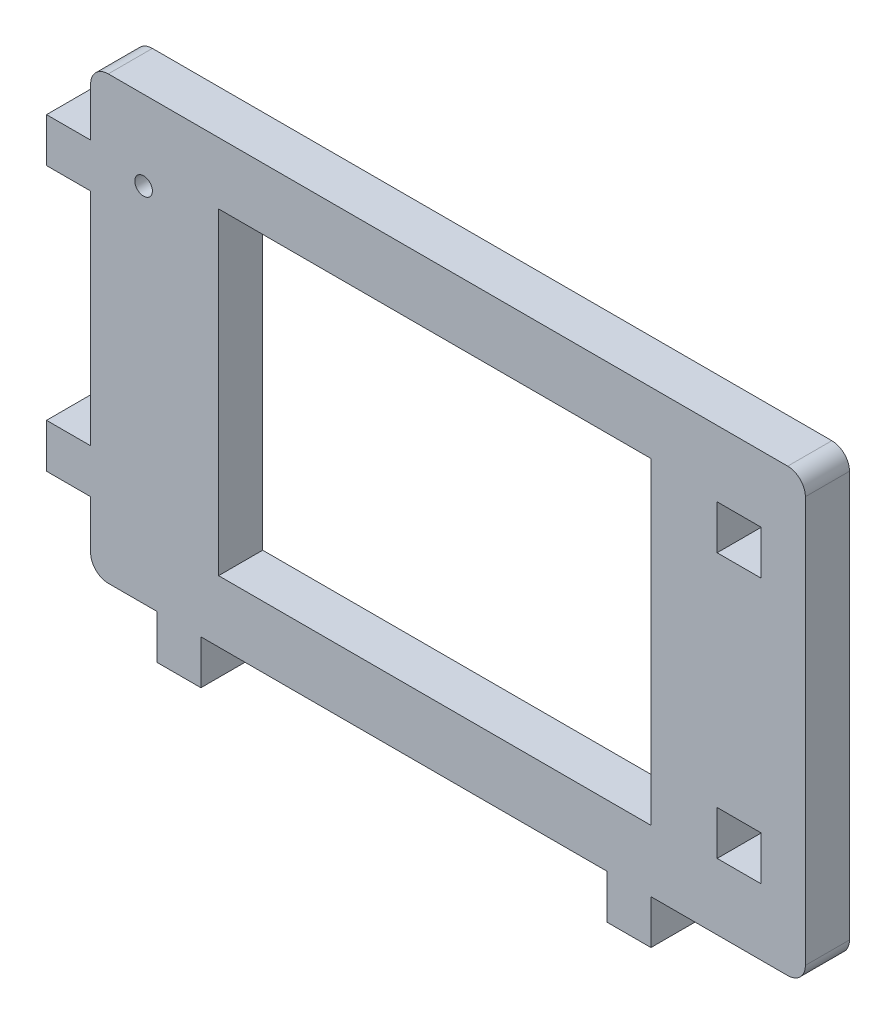
SolidWorks part; units mm, degrees
ref_plane "Plan de face" through (0, 0, 0) normal (0, 0, 1) x (1, 0, 0)
ref_plane "Plan de dessus" through (0, 0, 0) normal (0, 1, 0) x (1, 0, 0)
ref_plane "Plan de droite" through (0, 0, 0) normal (1, 0, 0) x (0, 0, -1)
sketch "Esquisse1" plane through (0, 0, 0) normal (0, 0, 1) x (1, 0, 0)
  line L0 (0, 25) -> (71, 25) construction
  line L1 (0, 0) -> (7.5, 0)
  line L2 (0, 0) -> (0, 7.5)
  line L3 (0, 50) -> (71, 50)
  line L4 (71, 0) -> (71, 7.5) construction
  line L5 (0, 12.5) -> (-5, 12.5)
  line L7 (0, 7.5) -> (-5, 7.5)
  line L8 (-5, 12.5) -> (-5, 7.5)
  line L9 (35.5, 0) -> (35.5, 50) construction
  line L10 (0, 37.5) -> (-5, 37.5)
  line L11 (-5, 37.5) -> (-5, 42.5)
  line L12 (0, 42.5) -> (-5, 42.5)
  line L13 (58.5, 0) -> (58.5, -5)
  line L15 (7.5, 0) -> (7.5, -5)
  line L16 (7.5, -5) -> (12.5, -5)
  line L17 (12.5, 0) -> (12.5, -5)
  line L18 (63.5, -5) -> (58.5, -5)
  line L19 (63.5, 0) -> (63.5, -5)
  line L20 (71, 7.5) -> (76, 7.5)
  line L21 (76, 12.5) -> (76, 7.5)
  line L22 (71, 12.5) -> (76, 12.5)
  line L23 (71, 37.5) -> (76, 37.5)
  line L24 (76, 37.5) -> (76, 42.5)
  line L25 (71, 42.5) -> (76, 42.5)
  line L26 (0, 42.5) -> (0, 50)
  line L27 (0, 12.5) -> (0, 37.5)
  line L28 (12.5, 0) -> (58.5, 0)
  line L29 (63.5, 0) -> (71, 0)
  line L30 (71, 12.5) -> (71, 37.5) construction
  line L31 (71, 42.5) -> (71, 50) construction
  line L32 (71, 50) -> (81, 50)
  line L33 (14.5, 43) -> (63.5, 43)
  line L34 (14.5, 43) -> (14.5, 7)
  line L35 (14.5, 7) -> (63.5, 7)
  line L36 (63.5, 43) -> (63.5, 7)
  line L37 (81, 50) -> (81, 0)
  line L38 (81, 0) -> (71, 0)
  line L39 (71, 42.5) -> (71, 37.5)
  line L40 (71, 12.5) -> (71, 7.5)
  circle A0 centre (6, 41) radius 1
  point P37 (63.5, 25)
  dimension "D8" = 2
  dimension "D9" = 6
  dimension "D1" = 71
  dimension "D2" = 50
  dimension "D3" = 5
  dimension "D4" = 7.5
  dimension "D5" = 7.5
  dimension "D6" = 36
  dimension "D7" = 49
  dimension "D10" = 9
  dimension "D11" = 7.5
  dimension "D12" = 5
extrude "Boss.-Extru.1" add sketch "Esquisse1" along normal blind 5
fillet "Congé1" radius 2 4 edges at (0, 0, 2.5) (0, 50, 2.5) (81, 0, 2.5) (81, 50, 2.5)
